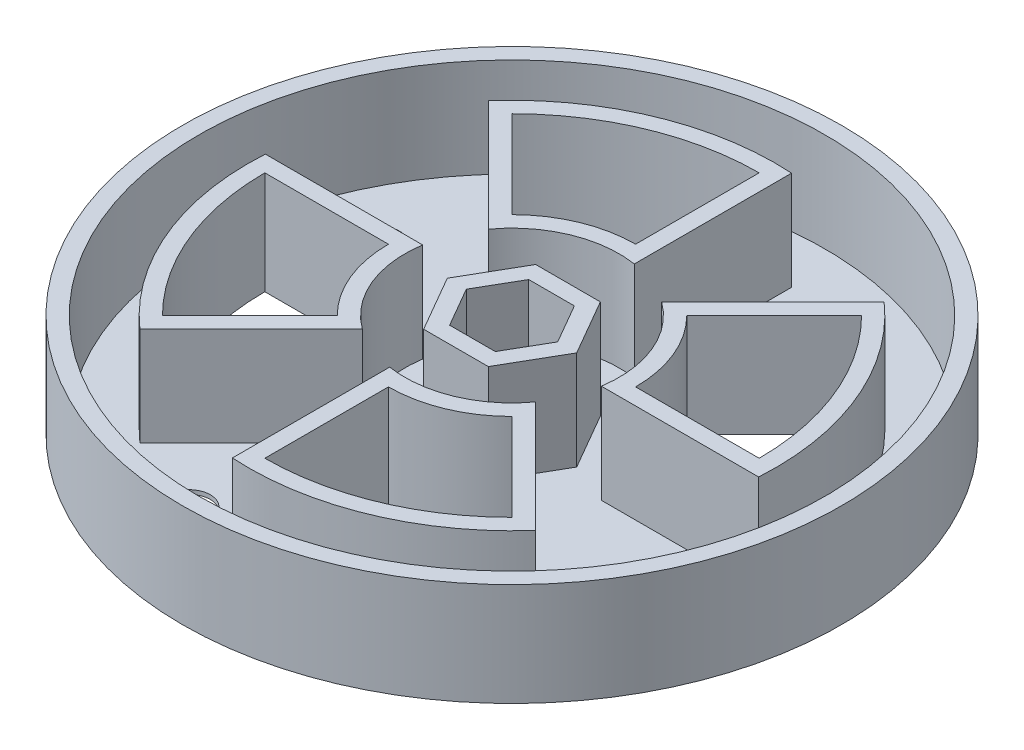
SolidWorks part; units mm, degrees
ref_plane "Front Plane" through (0, 0, 0) normal (0, 0, 1) x (1, 0, 0)
ref_plane "Top Plane" through (0, 0, 0) normal (0, 1, 0) x (1, 0, 0)
ref_plane "Right Plane" through (0, 0, 0) normal (1, 0, 0) x (0, 0, -1)
sketch "Sketch1" plane through (0, 0, 0) normal (0, 1, 0) x (1, 0, 0)
  circle A0 centre (0, 0) radius 50.8
  dimension "D1" = 101.6
extrude "Boss-Extrude1" add sketch "Sketch1" along normal blind 15.875
sketch "Sketch4" plane through (0, 15.875, 0) normal (0, 1, 0) x (1, 0, 0)
  line L0 (-3.5195, 6.096) -> (3.5195, 6.096)
  line L1 (3.5195, 6.096) -> (7.0391, 0)
  line L2 (7.0391, 0) -> (3.5195, -6.096)
  line L3 (3.5195, -6.096) -> (-3.5195, -6.096)
  line L4 (-3.5195, -6.096) -> (-7.0391, 0)
  line L5 (-7.0391, 0) -> (-3.5195, 6.096)
  point P7 (0, 6.096)
  dimension "D1" = 120
  dimension "D2" = 12.192
extrude "Cut-Extrude2" cut sketch "Sketch4" against normal blind 15.24 contours L5 L0 L1 L2 L3 L4
sketch "Sketch5" plane through (0, 0.635, 0) normal (0, 1, 0) x (1, 0, 0)
  circle A0 centre (0, 0) radius 4.191
  dimension "D1" = 8.382
extrude "Cut-Extrude3" cut sketch "Sketch5" against normal through all contours A0
sketch "Sketch6" plane through (0, 15.875, 0) normal (0, 1, 0) x (1, 0, 0)
  line L0 (0, 0) -> (0, 38.1)
  line L1 (0, 0) -> (26.9408, 26.9408)
  line L2 (0, 0) -> (38.1, 0)
  line L3 (0, 0) -> (26.9408, -26.9408)
  line L4 (0, 0) -> (0, -38.1)
  line L5 (0, 0) -> (-26.9408, -26.9408)
  line L6 (0, 0) -> (-38.1, 0)
  line L7 (0, 0) -> (-26.9408, 26.9408)
  circle A0 centre (0, 0) radius 38.1
  circle A1 centre (0, 0) radius 19.05
  point P15 (0, 0)
  dimension "D1" = 38.1
  dimension "D2" = 76.2
  dimension "D3" = 45
  dimension "D4" = 4
extrude "Cut-Extrude4" cut sketch "Sketch6" against normal through all contours A1 L0 A0 L7 | A1 L2 A0 L1 | A1 L4 A0 L3 | A1 L6 A0 L5
sketch "Sketch7" plane through (0, 15.875, 0) normal (0, 1, 0) x (1, 0, 0)
  line L27 (16.3134, -2.54) -> (40.5605, -2.54)
  line L28 (26.8846, 30.4767) -> (9.7393, 13.3314)
  line L29 (2.54, 16.3134) -> (2.54, 40.5605)
  line L30 (-30.4767, 26.8846) -> (-13.3314, 9.7393)
  line L31 (2.54, 16.3134) -> (2.54, 40.5605)
  line L32 (-30.4767, 26.8846) -> (-13.3314, 9.7393)
  line L33 (-2.54, -16.3134) -> (-2.54, -40.5605)
  line L34 (30.4767, -26.8846) -> (13.3314, -9.7393)
  line L35 (-16.3134, 2.54) -> (-40.5605, 2.54)
  line L36 (-26.8846, -30.4767) -> (-9.7393, -13.3314)
  line L64 (9.972, 0) -> (4.986, 8.636)
  line L65 (4.986, -8.636) -> (9.972, 0)
  line L66 (-4.986, -8.636) -> (4.986, -8.636)
  line L67 (-9.972, 0) -> (-4.986, -8.636)
  line L68 (-4.986, 8.636) -> (-9.972, 0)
  line L69 (4.986, 8.636) -> (-4.986, 8.636)
  line L70 (9.972, 0) -> (4.986, 8.636)
  line L71 (4.986, -8.636) -> (9.972, 0)
  line L72 (-4.986, -8.636) -> (4.986, -8.636)
  line L73 (-9.972, 0) -> (-4.986, -8.636)
  line L74 (-4.986, 8.636) -> (-9.972, 0)
  line L75 (4.986, 8.636) -> (-4.986, 8.636)
  arc A28 (40.5605, -2.54) -> (26.8846, 30.4767) centre (0, 0) ccw
  arc A29 (16.3134, -2.54) -> (9.7393, 13.3314) centre (0, 0) ccw
  arc A30 (2.54, 16.3134) -> (-13.3314, 9.7393) centre (0, 0) ccw
  arc A31 (2.54, 40.5605) -> (-30.4767, 26.8846) centre (0, 0) ccw
  arc A32 (2.54, 16.3134) -> (-13.3314, 9.7393) centre (0, 0) ccw
  arc A33 (2.54, 40.5605) -> (-30.4767, 26.8846) centre (0, 0) ccw
  arc A34 (-2.54, -40.5605) -> (30.4767, -26.8846) centre (0, 0) ccw
  arc A35 (-2.54, -16.3134) -> (13.3314, -9.7393) centre (0, 0) ccw
  arc A36 (-40.5605, 2.54) -> (-26.8846, -30.4767) centre (0, 0) ccw
  arc A37 (-16.3134, 2.54) -> (-9.7393, -13.3314) centre (0, 0) ccw
  circle A40 centre (0, 0) radius 48.26
  circle A41 centre (0, 0) radius 50.8 construction
  point P15 (0, 0)
  dimension "D4" = 2.54
  dimension "D1" = 2.54
  dimension "D3" = 2.54
  dimension "D2" = 4
extrude "Cut-Extrude5" cut sketch "Sketch7" against normal up to surface (15.24 mm away) contours A40 L35 A37 L36 A36 L27 A29 L28 A28 L75 L70 L71 L72 L73 L74 A33 L31 A32 L32 L33 A35 L34 A34 up to face at (0, 0.635, 4.191)
sketch "Sketch8" plane through (0, 0, 0) normal (0, -1, 0) x (1, 0, 0)
  line L0 (0, 0) -> (0, 38.1) construction
  line L1 (0, 0) -> (-26.9408, 26.9408) construction
  line L2 (-14.5802, 35.1998) -> (0, 0) construction
  circle A0 centre (-14.5802, 35.1998) radius 3.2639
  circle A4 centre (35.1998, 14.5802) radius 3.2639
  circle A5 centre (14.5802, -35.1998) radius 3.2639
  circle A6 centre (-35.1998, -14.5802) radius 3.2639
  point P2 (0, 0)
  point P3 (-52.0582, -21.8924)
  point P4 (0, 0)
  point P17 (0, 0)
  dimension "D1" = 6.5278
  dimension "D2" = 22.5
  dimension "D3" = 38.1
  dimension "D4" = 4
extrude "Cut-Extrude6" cut sketch "Sketch8" against normal through all contours A6 | A4 | A5 | A0
